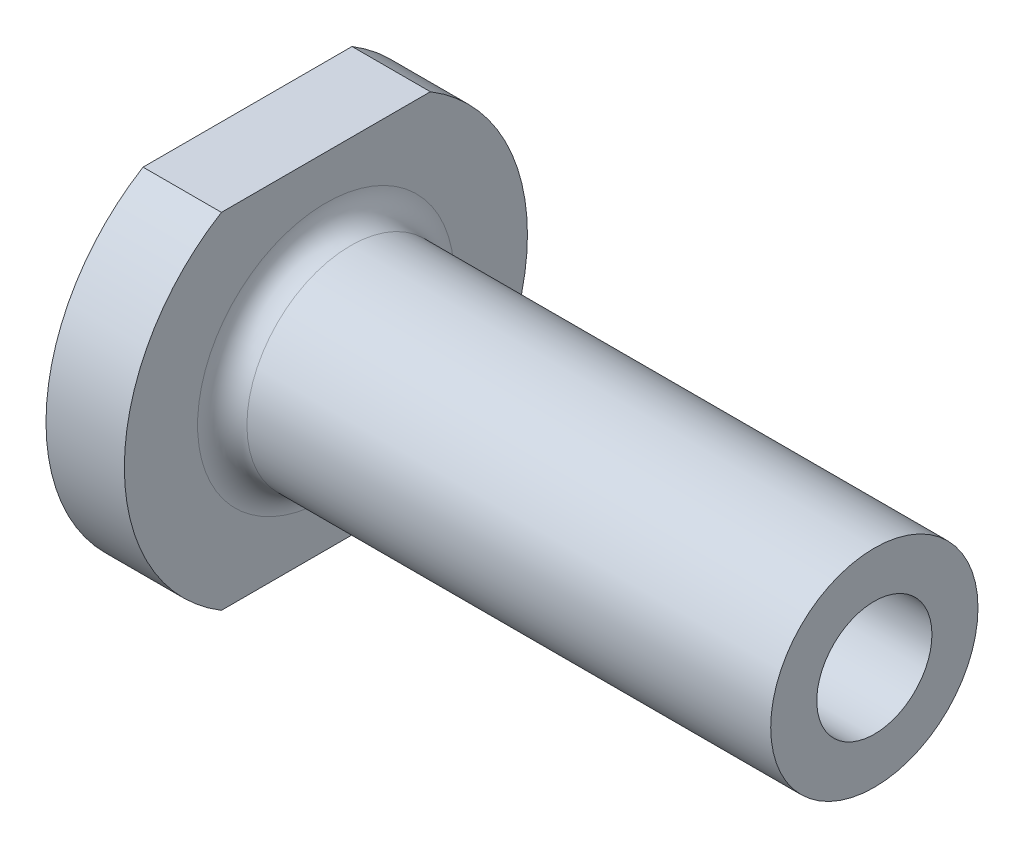
SolidWorks part; units mm, degrees
material "Ti-6Al-4VSolution treated and aged (SS)"
ref_plane "Front Plane" through (0, 0, 0) normal (0, 0, 1) x (1, 0, 0)
ref_plane "Top Plane" through (0, 0, 0) normal (0, 1, 0) x (1, 0, 0)
ref_plane "Right Plane" through (0, 0, 0) normal (1, 0, 0) x (0, 0, -1)
sketch "Sketch1" plane through (0, 0, 0) normal (0, 0, 1) x (1, 0, 0)
  line L0 (0, 0) -> (-17.6508, 0) construction
  line L1 (0, 0) -> (38.1, 0)
  line L2 (38.1, 0) -> (38.1, 6.3)
  line L3 (38.1, 6.3) -> (4.7625, 6.3)
  line L4 (4.7625, 6.3) -> (4.7625, 12.25)
  line L5 (4.7625, 12.25) -> (0, 12.25)
  line L6 (0, 12.25) -> (0, 0)
  dimension "D1" = 12.6
  dimension "D2" = 38.1
  dimension "D3" = 4.7625
  dimension "D4" = 24.5
revolve "Revolve1" add sketch "Sketch1" angle 360 about L0
fillet "Fillet1" radius 1.5 1 edges at (4.7625, 0, -6.3)
hole_wizard "5/16-18 MAKE SURE TO CHANGE THIS" positions "Sketch2" profile "Sketch3" tap size "M8x1.0" standard "ANSI Metric" end condition through all
sketch "Sketch2" plane through (38.1, 0, 0) normal (1, 0, 0) x (0, 0, -1)
  point P0 (0, 0)
sketch "Sketch3" plane through (38.1, 0, 0) normal (0, 1, 0) x (0, 0, -1)
  line L0 (0, 0) -> (0, 38.1)
  line L1 (0, 38.1) -> (3.5, 38.1)
  line L2 (3.5, 38.1) -> (3.5, 0)
  line L5 (3.5, 0) -> (0, 0)
  line L11 (0, -6.35) -> (0, 107.95) construction
  dimension "Thru Tap Drill Dia." = 7
  dimension "Thru Tap Drill Depth" = 38.1
cosmetic thread "Hole Thread1" parameters "D2"=8
sketch "Sketch4" plane through (0, 0, 0) normal (-1, 0, 0) x (0, 0, 1)
  line L0 (-6.35, 10.4757) -> (6.35, 10.4757)
  line L5 (6.35, -10.4757) -> (-6.35, -10.4757)
  arc A1 (6.35, 10.4757) -> (-6.35, 10.4757) centre (0, 0) ccw
  circle A2 centre (0, 0) radius 12.25
  arc A3 (-6.35, -10.4757) -> (6.35, -10.4757) centre (0, 0) ccw
  dimension "D1" = 0
  dimension "D2" = 12.7
extrude "Cut-Extrude1" cut sketch "Sketch4" against normal through all
equation "\"D4@Sketch1\"=24.5mm"
equation "\"D1@Sketch1\"=0.500000in-0.1mm"
